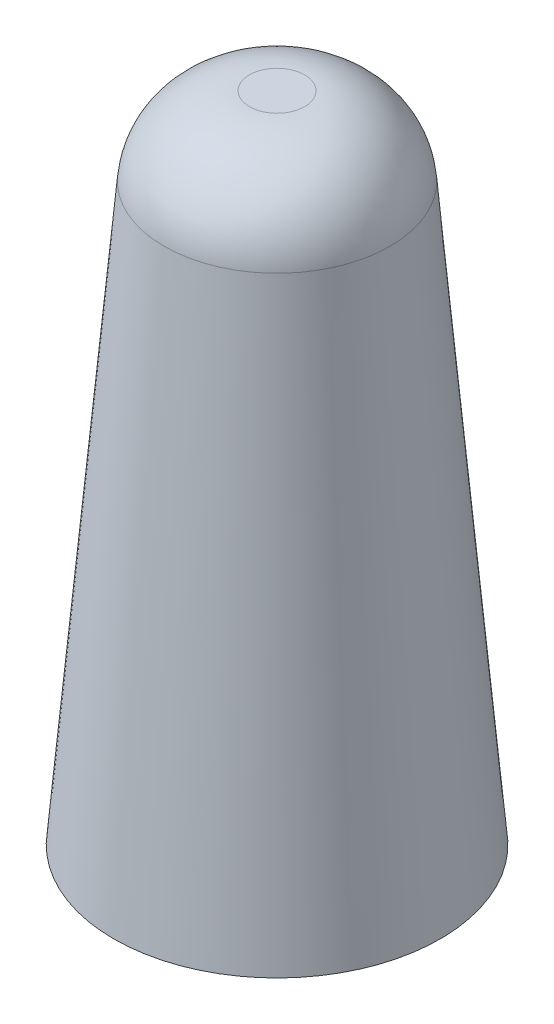
SolidWorks part; units mm, degrees
ref_plane "Alzado" through (0, 0, 0) normal (0, 0, 1) x (1, 0, 0)
ref_plane "Planta" through (0, 0, 0) normal (0, 1, 0) x (1, 0, 0)
ref_plane "Vista lateral" through (0, 0, 0) normal (1, 0, 0) x (0, 0, -1)
sketch "Croquis1" plane through (0, 0, 0) normal (0, 1, 0) x (1, 0, 0)
  circle A0 centre (0, 0) radius 19.05
  dimension "D1" = 38.1
extrude "Saliente-Extruir1" add sketch "Croquis1" along normal blind 76.2 draft 5
fillet "Redondeo1" radius 10 1 edges at (0, 76.2, 12.3834)
